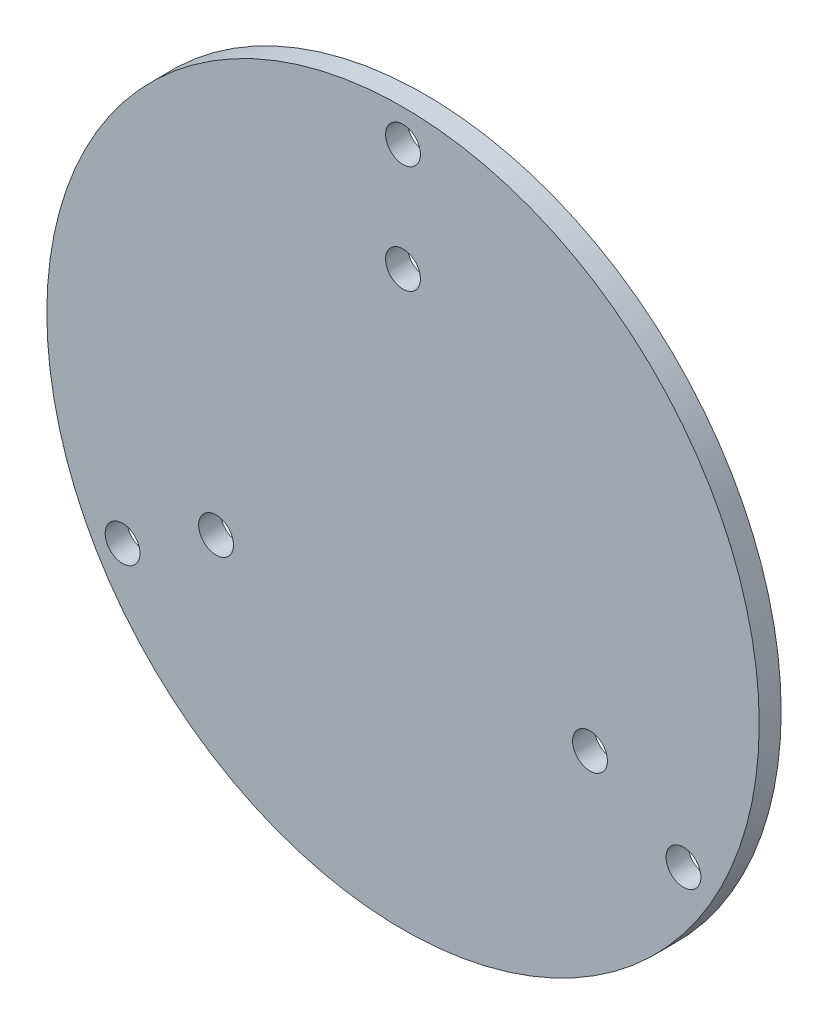
SolidWorks part; units mm, degrees
ref_plane "Front Plane" through (0, 0, 0) normal (0, 0, 1) x (1, 0, 0)
ref_plane "Top Plane" through (0, 0, 0) normal (0, 1, 0) x (1, 0, 0)
ref_plane "Right Plane" through (0, 0, 0) normal (1, 0, 0) x (0, 0, -1)
sketch "Sketch1" plane through (0, 0, 0) normal (0, 0, 1) x (1, 0, 0)
  circle A0 centre (0, 0) radius 16.5
  dimension "D1" = 33
extrude "Extrude1" add sketch "Sketch1" along normal blind 1.016
sketch "Sketch2" plane through (0, 0, 1.016) normal (0, 0, 1) x (1, 0, 0)
  circle A0 centre (0, 0) radius 2.5
  circle A1 centre (0, 0) radius 3
  circle A2 centre (0, 0) radius 8
  circle A3 centre (0, 0) radius 8.5
  circle A4 centre (0, 0) radius 16
  circle A5 centre (0, 0) radius 16.5 construction
  dimension "D1" = 0.5
  dimension "D2" = 0.5
  dimension "D3" = 0.5
  dimension "D4" = 5
  dimension "D5" = 5
  dimension "D6" = 7.5
sketch "Sketch4" plane through (0, 0, 0) normal (0, 0, -1) x (-1, 0, 0)
  circle A0 centre (0, 0) radius 10 construction
  point P3 (0, 10)
  point P4 (8.6603, -5)
  point P7 (-8.6603, -5)
  dimension "D1" = 20
  dimension "D2" = 3
hole_wizard "#0 Clearance Hole1" positions "3DSketch1" profile "Sketch5" hole size "#0" standard "Ansi Inch" end condition through all
sketch3d "3DSketch1"
  point P0 (0, 10, 0)
  point P3 (-8.6603, -5, 0)
  point P6 (8.6603, -5, 0)
sketch "Sketch5" plane through (0, 10, 0) normal (1, 0, 0) x (0, 1, 0)
  line L0 (0, 0) -> (0, 1.016)
  line L1 (0, 1.016) -> (0.8064, 1.016)
  line L2 (0.8064, 1.016) -> (0.8065, 0)
  line L5 (0.8065, 0) -> (0, 0)
  line L11 (0, -6.35) -> (0, 107.95) construction
  dimension "Thru Hole Dia." = 1.6129
  dimension "Thru Hole Depth" = 1.016
sketch "Sketch6" plane through (0, 0, 1.016) normal (0, 0, 1) x (1, 0, 0)
  line L0 (0, 0) -> (0, -15) construction
  circle A0 centre (0, 0) radius 15
  circle A1 centre (0, 0) radius 16.5
  circle A2 centre (0, 0) radius 16.5
  circle A3 centre (0, 15) radius 0.8065
  circle A4 centre (0, -15) radius 0.8065
  circle A5 centre (12.9904, 7.5) radius 0.8065
  circle A6 centre (-12.9904, 7.5) radius 0.8065
  circle A7 centre (12.9904, -7.5) radius 0.8065
  circle A8 centre (12.9904, 7.5) radius 0.8065
  circle A9 centre (0, -15) radius 0.8065
  circle A10 centre (0, 15) radius 0.8065 [skipped]
  circle A11 centre (12.9904, -7.5) radius 0.8065 [skipped]
  circle A12 centre (-12.9904, -7.5) radius 0.8064 [skipped]
  circle A13 centre (-12.9904, -7.5) radius 0.8065
  dimension "D2" = 30
  dimension "D3" = 1.6129
  dimension "D1" = 0
  dimension "D4" = 6
  dimension "D5" = 6
extrude "Cut-Extrude1" cut sketch "Sketch6" against normal blind 5 contours A0 A13 | A0 A13 | A0 A7 | A0 A7 | A0 A3 | A0 A3 | A4
